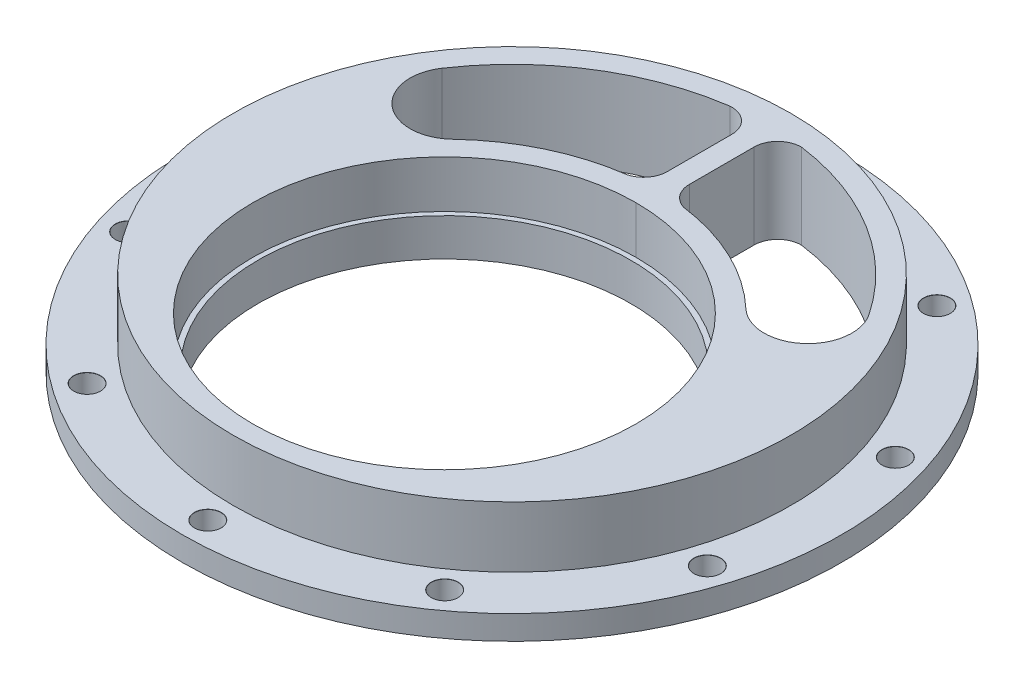
SolidWorks part; units mm, degrees
material "7075-T6, Plate (SS)"
ref_plane "X-Y Datum" through (0, 0, 0) normal (0, 0, 1) x (1, 0, 0)
ref_plane "X-Z Datum" through (0, 0, 0) normal (0, 1, 0) x (1, 0, 0)
ref_plane "Y-Z Datum" through (0, 0, 0) normal (1, 0, 0) x (0, 0, -1)
sketch "Sketch1" plane through (0, 0, 0) normal (0, 1, 0) x (1, 0, 0)
  line L0 (0, 0) -> (0, -12.7) construction
  line L1 (0, -43.0151) -> (0, 43.0151) construction
  line L2 (0, 61.9125) -> (0, 52.3875)
  circle A0 centre (0, -12.7) radius 35.052
  circle A1 centre (0, 0) radius 52.3875 construction
  circle A2 centre (0, 0) radius 57.15 construction
  circle A3 centre (0, 0) radius 61.9125
  point P12 (0, 57.15)
  dimension "D2" = 70.104
  dimension "D3" = 104.775
  dimension "D4" = 123.825
  dimension "D5" = 114.3
  dimension "D1" = 12.7
extrude "Boss-Extrude1" add sketch "Sketch1" along normal blind 4.5212
sketch "Sketch3" plane through (0, 4.5212, 0) normal (0, 1, 0) x (1, 0, 0)
  circle A0 centre (0, 0) radius 52.3875 construction
  circle A1 centre (0, 0) radius 52.3875
extrude "Boss-Extrude2" add sketch "Sketch3" along normal blind 11.43
sketch "Sketch4" plane through (0, 0, 0) normal (0, -1, 0) x (1, 0, 0)
  circle A0 centre (0, 12.7) radius 35.052 construction
  circle A1 centre (0, 12.7) radius 35.052
extrude "Cut-Extrude1" cut sketch "Sketch4" against normal through all
sketch "Sketch9" plane through (0, 15.9512, 0) normal (0, 1, 0) x (1, 0, 0)
  circle A0 centre (0, -12.7) radius 35.052 construction
  circle A1 centre (0, -12.7) radius 35.052 construction
  circle A2 centre (0, -12.7) radius 36
  dimension "D1" = 72
extrude "Cut-Extrude3" cut sketch "Sketch9" against normal blind 8.89
hole_wizard "Ø5.0mm Dowel Hole1" positions "Sketch7" profile "Sketch8" hole size "Ø5.0" standard "ANSI Metric" end condition through all
sketch "Sketch7" plane through (0, 4.5212, 0) normal (0, 1, 0) x (1, 0, 0)
  point P0 (0, 57.15)
sketch "Sketch8" plane through (0, 4.5212, -57.15) normal (1, 0, 0) x (0, 0, 1)
  line L0 (0, 0) -> (0, 4.5212)
  line L1 (0, 4.5212) -> (2.5, 4.5212)
  line L2 (2.5, 4.5212) -> (2.5, 0.025)
  line L3 (2.5, 0.025) -> (2.525, 0)
  line L5 (2.525, 0) -> (0, 0)
  line L6 (-2.5, 0.025) -> (-2.525, 0) construction
  line L11 (0, -6.35) -> (0, 107.95) construction
  dimension "Thru Hole Dia." = 5
  dimension "Thru Hole Depth" = 4.5212
  dimension "Near C'Sink Dia." = 5.05
  dimension "Near C'Sink Angle" = 90
pattern_circular "CirPattern1" count 10 over 360 about axis through (0, 0, 0) along (0, 1, 0) of "Ø5.0mm Dowel Hole1"
ref_point "Point1"
ref_plane "Plane1" through (0, 0, 0) normal (1, 0, 0) x (0, 0, -1)
split line "Split Line1"
ref_plane "Plane2" through (0, 7.9756, 0) normal (0, 1, 0) x (1, 0, 0)
sketch "Sketch14" plane through (0, 7.9756, 0) normal (0, 1, 0) x (1, 0, 0)
  circle A0 centre (-33.2491, 22.3603) radius 8.255
ref_point "Point4"
sketch "Sketch10" plane through (0, 15.9512, 0) normal (0, 1, 0) x (1, 0, 0)
  circle A0 centre (0, 0) radius 52.3875 construction
  circle A1 centre (0, 0) radius 52.3875 construction
  circle A3 centre (-33.2491, 22.3603) radius 8.255 construction
  circle A4 centre (33.2491, 22.3603) radius 8.255 construction
  arc A7 (0, -52.764) -> (0, 27.364) centre (0, -12.7) ccw
  arc A8 (0, 27.364) -> (0, -52.764) centre (0, -12.7) ccw
  arc A9 (0, -52.764) -> (0, 27.364) centre (0, -12.7) ccw construction
  arc A10 (0, 27.364) -> (0, -52.764) centre (0, -12.7) ccw construction
  circle A29 centre (0, 0) radius 48.3235 construction
  arc A30 (-27.5687, 16.3704) -> (27.5687, 16.3704) centre (0, -12.7) cw
  arc A31 (-40.0992, 26.967) -> (40.0992, 26.967) centre (0, 0) cw
  arc A32 (-40.0992, 26.967) -> (-27.5687, 16.3704) centre (-33.2491, 22.3603) ccw
  arc A33 (27.5687, 16.3704) -> (40.0992, 26.967) centre (33.2491, 22.3603) ccw
  dimension "D3" = 16.51
  dimension "D1" = 4.064
  dimension "D2" = 4.064
extrude "Cut-Extrude5" cut sketch "Sketch10" against normal through all contours A33 A31 A32 A30
sketch "Sketch15" plane through (0, 7.9756, 0) normal (0, 1, 0) x (1, 0, 0)
  line L1 (-2.1171, 31.2835) -> (-2.1171, 43.3958)
  line L4 (2.032, 31.291) -> (2.032, 43.4389)
  line L6 (-2.1764, 48.3235) -> (-2.1667, 48.2749) construction
  line L8 (2.1667, 48.2749) -> (2.1764, 48.3235) construction
  arc A0 (27.5687, 16.3704) -> (-27.5687, 16.3704) centre (0, -12.7) ccw construction
  arc A1 (27.5687, 16.3704) -> (-27.5687, 16.3704) centre (0, -12.7) ccw construction
  arc A2 (40.0992, 26.967) -> (-40.0992, 26.967) centre (0, 0) ccw construction
  arc A3 (-2.1171, 43.3958) -> (-6.9062, 47.8275) centre (-6.5621, 43.3958) ccw
  arc A4 (40.0992, 26.967) -> (-40.0992, 26.967) centre (0, 0) ccw construction
  arc A5 (6.5037, 47.8838) -> (2.032, 43.4389) centre (6.477, 43.4389) ccw
  arc A7 (-2.1171, 31.2835) -> (-5.362, 27.0036) centre (-6.5621, 31.2835) cw
  arc A9 (2.032, 31.291) -> (5.2509, 27.0184) centre (6.477, 31.291) ccw
  arc A10 (-6.9062, 47.8275) -> (6.5037, 47.8838) centre (0, 0) cw
  arc A11 (-5.362, 27.0036) -> (5.2509, 27.0184) centre (0, -12.7) cw
  point P9 (0, 37.4715)
  dimension "D1" = 4.445
  dimension "D2" = 2.1171
  dimension "D3" = 4.445
  dimension "D4" = 2.032
  dimension "D5" = 43.4389
  dimension "D6" = 31.2835
  dimension "D7" = 2.1171
  dimension "D8" = 12.148
  dimension "D9" = 12.1123
extrude "Boss-Extrude3" add sketch "Sketch15" along normal up to surface and the other way up to surface contours A9 L4 A5 A10 A3 L1 A7 A11 up to face at (0, 15.9512, -26.9504) other way up to face at (0, 0, -26.9504)
sketch "Sketch20" plane through (0, 4.5212, 0) normal (0, 1, 0) x (1, 0, 0)
  circle A0 centre (0, 0) radius 52.3875
  circle A2 centre (0, 0) radius 66.6087
sketch "Sketch25" plane through (0, 15.9512, 0) normal (0, 1, 0) x (1, 0, 0)
  line L6 (-4.6571, 31.2835) -> (-4.6571, 43.3958)
  line L7 (-4.6571, 31.2835) -> (-4.6571, 43.3958)
  line L12 (4.572, 43.4389) -> (4.572, 31.291)
  line L13 (4.572, 43.4389) -> (4.572, 31.291)
  circle A1 centre (-51.685, -7.6867) radius 0.134
  circle A2 centre (49.3335, -18.9489) radius 0.46
  arc A3 (48.8818, -18.8622) -> (48.9404, -18.71) centre (-0.2183, 0.1504) ccw
  arc A4 (48.8818, -18.8622) -> (48.9404, -18.71) centre (-0.2183, 0.1504) ccw
  arc A45 (-4.6571, 43.3958) -> (-6.6423, 45.2991) centre (-6.5621, 43.3958) ccw
  arc A46 (-5.9167, 29.4912) -> (-4.6571, 31.2835) centre (-6.5621, 31.2835) ccw
  arc A47 (-5.9167, 29.4912) -> (-29.3165, 18.2135) centre (0, -12.7) ccw
  arc A48 (-37.9914, 25.5495) -> (-29.3165, 18.2135) centre (-33.2491, 22.3603) ccw
  arc A49 (-6.6423, 45.2991) -> (-37.9914, 25.5495) centre (0, 0) ccw
  arc A50 (-4.6571, 43.3958) -> (-6.6423, 45.2991) centre (-6.5621, 43.3958) ccw
  arc A51 (-5.9167, 29.4912) -> (-4.6571, 31.2835) centre (-6.5621, 31.2835) ccw
  arc A52 (-5.9167, 29.4912) -> (-29.3165, 18.2135) centre (0, -12.7) ccw
  arc A53 (-37.9914, 25.5495) -> (-29.3165, 18.2135) centre (-33.2491, 22.3603) ccw
  arc A54 (-6.6423, 45.2991) -> (-37.9914, 25.5495) centre (0, 0) ccw
  circle A68 centre (-0.2183, 0.1504) radius 52.1224
  circle A69 centre (0, -12.7) radius 32.512
  circle A70 centre (0, -12.7) radius 32.512
  arc A72 (29.3165, 18.2135) -> (37.9914, 25.5495) centre (33.2491, 22.3603) ccw
  arc A73 (4.572, 31.291) -> (5.8124, 29.5056) centre (6.477, 31.291) ccw
  arc A74 (29.3165, 18.2135) -> (5.8124, 29.5056) centre (0, -12.7) ccw
  arc A75 (37.9914, 25.5495) -> (6.3564, 45.3401) centre (0, 0) ccw
  arc A76 (6.3564, 45.3401) -> (4.572, 43.4389) centre (6.477, 43.4389) ccw
  arc A77 (29.3165, 18.2135) -> (37.9914, 25.5495) centre (33.2491, 22.3603) ccw
  arc A78 (4.572, 31.291) -> (5.8124, 29.5056) centre (6.477, 31.291) ccw
  arc A79 (29.3165, 18.2135) -> (5.8124, 29.5056) centre (0, -12.7) ccw
  arc A80 (37.9914, 25.5495) -> (6.3564, 45.3401) centre (0, 0) ccw
  arc A81 (6.3564, 45.3401) -> (4.572, 43.4389) centre (6.477, 43.4389) ccw
  arc M3 (27.5687, 16.3704) -> (5.2509, 27.0184) centre (0, -12.7) ccw
  arc M4 (5.2509, 27.0184) -> (2.032, 31.291) centre (6.477, 31.291) cw
  line M5 (2.032, 31.291) -> (2.032, 43.4389)
  arc M6 (2.032, 43.4389) -> (6.5037, 47.8838) centre (6.477, 43.4389) cw
  arc M7 (6.5037, 47.8838) -> (40.0992, 26.967) centre (0, 0) cw
  arc M8 (40.0992, 26.967) -> (27.5687, 16.3704) centre (33.2491, 22.3603) cw
  arc M9 (-5.362, 27.0036) -> (-27.5687, 16.3704) centre (0, -12.7) ccw
  arc M10 (-27.5687, 16.3704) -> (-40.0992, 26.967) centre (-33.2491, 22.3603) cw
  arc M11 (-40.0992, 26.967) -> (-6.9062, 47.8275) centre (0, 0) cw
  arc M12 (-6.9062, 47.8275) -> (-2.1171, 43.3958) centre (-6.5621, 43.3958) cw
  line M13 (-2.1171, 43.3958) -> (-2.1171, 31.2835)
  arc M14 (-2.1171, 31.2835) -> (-5.362, 27.0036) centre (-6.5621, 31.2835) cw
  arc M15 (0, 23.3) -> (0, -48.7) centre (0, -12.7) cw
  arc M16 (0, -48.7) -> (0, 23.3) centre (0, -12.7) cw
  dimension "D1" = 2.54
  dimension "D2" = 2.54
  dimension "D3" = 2.54
extrude "Boss-Extrude5" [suppressed] add sketch "Sketch25" along normal blind 1.27 contours A54 A50 L7 A51 A52 A53 M9 M14 M13 M12 M11 M10 | A70 M15 M16 | A68 A1 M16 M15 M14 M9 M10 M11 M12 M13 M8 M3 M4 M5 M6 M7 | A81 A80 A77 A79 A78 L13 M3 M8 M7 M6 M5 M4
sketch "Sketch26" plane through (0, 4.5212, 0) normal (0, 1, 0) x (1, 0, 0)
  circle A2 centre (0, 0) radius 52.3875
  arc A3 (-46.0336, 25.0072) -> (-51.9408, 6.8266) centre (-49.7593, 16.1678) ccw
  arc A4 (-22.5431, 47.2891) -> (-38.0084, 36.0529) centre (-30.7529, 42.3278) ccw
  arc A5 (9.5581, 51.5082) -> (-9.5581, 51.5082) centre (0, 52.32) ccw
  arc A6 (38.0084, 36.0529) -> (22.5431, 47.2891) centre (30.7529, 42.3278) ccw
  arc A7 (51.9408, 6.8266) -> (46.0336, 25.0072) centre (49.7593, 16.1678) ccw
  arc A8 (46.0336, -25.0072) -> (51.9408, -6.8266) centre (49.7593, -16.1678) ccw
  arc A9 (22.5431, -47.2891) -> (38.0084, -36.0529) centre (30.7529, -42.3278) ccw
  arc A10 (-9.5581, -51.5082) -> (9.5581, -51.5082) centre (0, -52.32) ccw
  arc A11 (-38.0084, -36.0529) -> (-22.5431, -47.2891) centre (-30.7529, -42.3278) ccw
  arc A12 (-51.9408, -6.8266) -> (-46.0336, -25.0072) centre (-49.7593, -16.1678) ccw
  point P3 (-49.7593, 16.1678)
  point P37 (0, 0)
  circle M14 centre (0, 0) radius 61.9125
  dimension "D1" = 10
extrude "Cut-Extrude6" [suppressed] cut sketch "Sketch26" against normal through all both and the other way through all contours A4 A3 A2 M14 | A5 A4 A2 M14 | A6 A5 A2 M14 | A7 A6 A2 M14 | A8 A7 A2 M14 | A9 A8 A2 M14 | A10 A9 A2 M14 | A11 A10 A2 M14 | A12 A11 A2 M14 | A12 A2 A3 M14
fillet "Fillet1" [suppressed] radius 7.62
